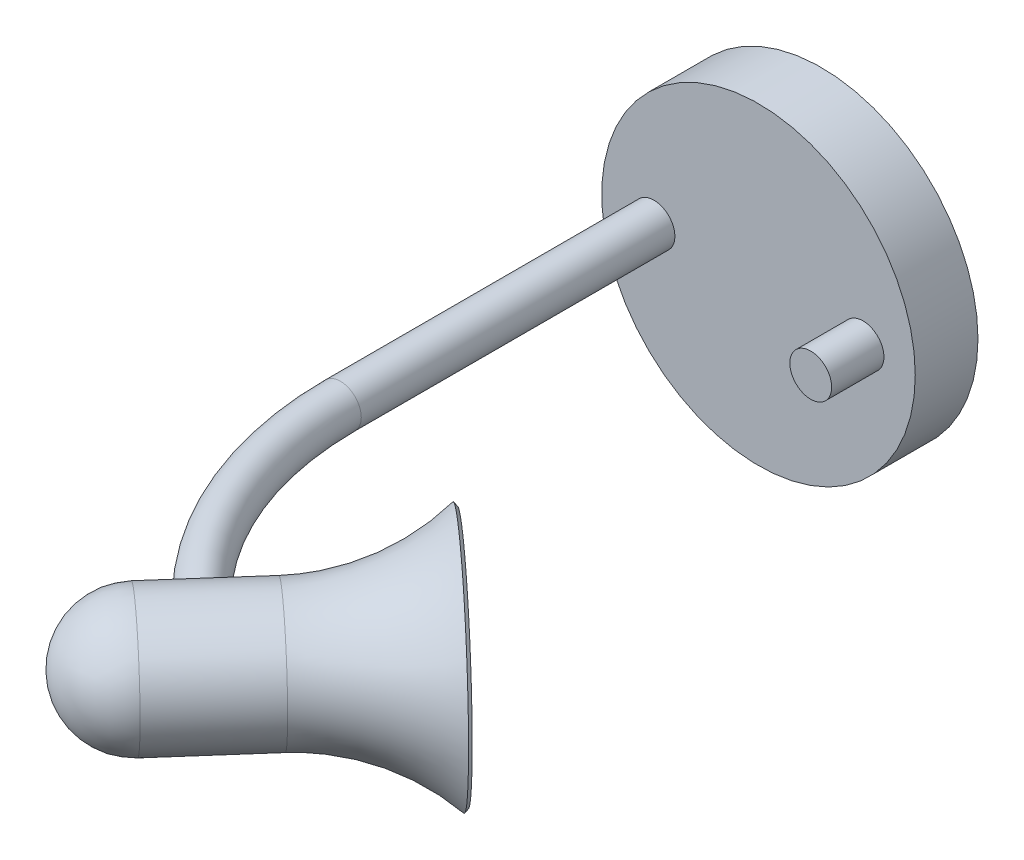
SolidWorks part; units mm, degrees
ref_plane "前视基准面" through (0, 0, 0) normal (0, 0, 1) x (1, 0, 0)
ref_plane "上视基准面" through (0, 0, 0) normal (0, 1, 0) x (1, 0, 0)
ref_plane "右视基准面" through (0, 0, 0) normal (1, 0, 0) x (0, 0, -1)
sketch "草图1" plane through (0, 0, 0) normal (0, 0, 1) x (1, 0, 0)
  circle A0 centre (0, 0) radius 75
  dimension "D1" = 150
extrude "凸台-拉伸1" add sketch "草图1" along normal blind 30
sketch "草图2" plane through (0, 0, 30) normal (0, 0, 1) x (1, 0, 0)
  line L0 (114.548, 0) -> (-127.9002, 0) construction
  circle A0 centre (50, 0) radius 10
  dimension "D1" = 20
  dimension "D2" = 50
extrude "凸台-拉伸2" add sketch "草图2" along normal blind 25
sketch "草图3" plane through (0, 0, 30) normal (0, 0, 1) x (1, 0, 0)
  line L0 (-98.6386, 0) -> (103.3245, 0) construction
  circle A0 centre (-50, 0) radius 10
  dimension "D1" = 20
  dimension "D2" = 50
sketch "草图4" plane through (0, 0, 0) normal (0, 1, 0) x (1, 0, 0)
  line L0 (-50, -30) -> (-50, -180)
  arc A0 (-50, -180) -> (4.1699, -300) centre (110, -180) ccw
  dimension "D1" = 160
  dimension "D2" = 150
  dimension "D3" = 120
sweep "扫描1" add profiles "草图3" path "草图4"
sketch "草图5" plane through (0, 0, 0) normal (0, 1, 0) x (1, 0, 0)
  line L0 (158.8341, -169.983) -> (-91.5779, -453.9236) construction
  line L1 (-2.4444, -307.5) -> (10.7843, -292.5) construction
  line L2 (20.7059, -281.25) -> (-12.366, -318.75)
  line L3 (-9.7091, -361.0931) -> (-61.9832, -314.9917) construction
  arc A0 (-12.366, -318.75) -> (-9.7091, -361.0931) centre (10.134, -338.5931) ccw
  arc A1 (20.7059, -281.25) -> (43.2047, -221.25) centre (-46.7941, -221.7206) ccw
  arc A2 (-60, -180) -> (-2.4444, -307.5) centre (110, -180) ccw construction
  point P9 (-2.4444, -307.5)
  dimension "D1" = 90
  dimension "D5" = 30
  dimension "D2" = 60
  dimension "D3" = 50
  dimension "D4" = 15
  dimension "D6" = 30
revolve "旋转-薄壁7" add sketch "草图5" angle 360 about L0 wall 2
